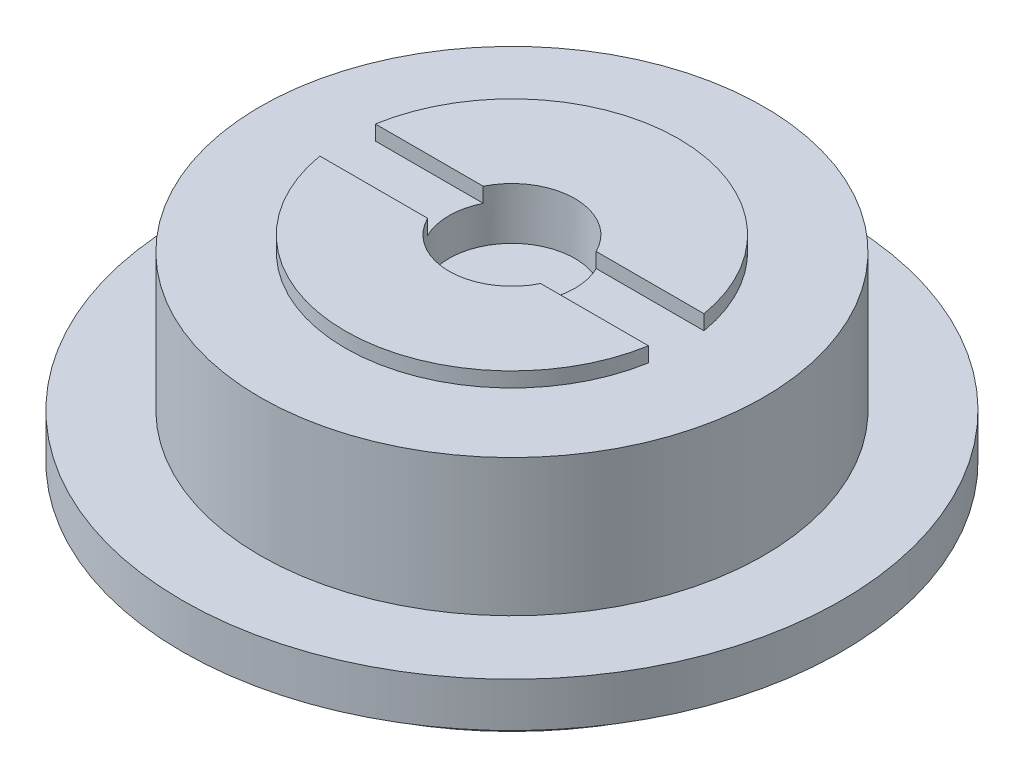
SolidWorks part; units mm, degrees
material "PP Copolymer"
ref_plane "Front Plane" through (0, 0, 0) normal (0, 0, 1) x (1, 0, 0)
ref_plane "Top Plane" through (0, 0, 0) normal (0, 1, 0) x (1, 0, 0)
ref_plane "Right Plane" through (0, 0, 0) normal (1, 0, 0) x (0, 0, -1)
sketch "BaseS" plane through (0, 0, 0) normal (0, 1, 0) x (1, 0, 0)
  circle A0 centre (0, 0) radius 8.9
  dimension "Dia" = 17.8
extrude "Base" add sketch "BaseS" against normal blind 1.2
sketch "O-RingCaptureS" plane through (0, 0, 0) normal (0, 1, 0) x (1, 0, 0)
  circle A0 centre (0, 0) radius 6.8
  circle A1 centre (0, 0) radius 8.9 construction
  dimension "RefDia" = 13.6
  dimension "DiaControl" = 2.1
extrude "O-RingCapture" add sketch "O-RingCaptureS" along normal blind 3.7
sketch "SealingFaceS" plane through (0, 3.7, 0) normal (0, 1, 0) x (1, 0, 0)
  circle A0 centre (0, 0) radius 4.5
  circle A1 centre (0, 0) radius 6.8 construction
  dimension "RefDia" = 9
  dimension "DiaControl" = 2.3
extrude "SealingFace" add sketch "SealingFaceS" along normal blind 0.4
sketch "SlotCutS" plane through (0, 4.1, 0) normal (0, 1, 0) x (1, 0, 0)
  line L1 (-4.5, 0.75) -> (4.5, 0.75)
  line L2 (-4.5, 0.75) -> (-4.5, -0.75)
  line L3 (-4.5, -0.75) -> (4.5, -0.75)
  line L4 (4.5, 0.75) -> (4.5, -0.75)
  line L5 (-4.5, 0.75) -> (4.5, -0.75) construction
  line L6 (-4.5, -0.75) -> (4.5, 0.75) construction
  circle A0 centre (0, 0) radius 4.5 construction
  point P0 (0, 0)
  dimension "SlotWidth" = 1.5
extrude "SlotCut" cut sketch "SlotCutS" against normal up to surface (0.4 mm away) up to face at (0, 3.7, 4.5)
sketch "BottomBaseS" plane through (0, -1.2, 0) normal (0, -1, 0) x (1, 0, 0)
  circle A0 centre (0, 0) radius 7.8
  circle A1 centre (0, 0) radius 8.9 construction
  dimension "RefDia" = 15.6
  dimension "DiaControl" = 1.1
extrude "BottomBase" add sketch "BottomBaseS" along normal blind 0.8
sketch "TopBoreS" plane through (0, 4.1, 0) normal (0, 1, 0) x (1, 0, 0)
  circle A0 centre (0, 0) radius 1.7
  dimension "Dia" = 3.4
extrude "TopBore" cut sketch "TopBoreS" against normal blind 1.4
sketch "BottomBoreS" plane through (0, -2, 0) normal (0, -1, 0) x (1, 0, 0)
  circle A0 centre (0, 0) radius 5.5
  circle A1 centre (0, 0) radius 7.8 construction
  dimension "RefDia" = 11
  dimension "DiaControl" = 2.3
extrude "BottomBore" cut sketch "BottomBoreS" against normal blind 4.4
sketch "CentralCylinderS" plane through (0, 2.4, 0) normal (0, -1, 0) x (-1, 0, 0)
  circle A0 centre (0, 0) radius 2.5
  dimension "Dia" = 5
extrude "CentralCylinder" add sketch "CentralCylinderS" along normal offset from surface (2.6 mm away) 1.8 up to face at (0, -2, -5.5)
sketch "CylinderBoreS" plane through (0, -0.2, 0) normal (0, -1, 0) x (-1, 0, 0)
  circle A0 centre (0, 0) radius 1.5
  circle A1 centre (0, 0) radius 2.5 construction
  dimension "RefDia" = 3
  dimension "DiaControl" = 1
extrude "CylinderBore" cut sketch "CylinderBoreS" against normal blind 0.6
sketch "RibS" plane through (0, 2.4, 0) normal (0, -1, 0) x (-1, 0, 0)
  line L0 (0, 0) -> (0, -2.5) construction
  line L2 (0.625, -5.4644) -> (0.625, -2.4206)
  line L4 (-0.625, -5.4644) -> (-0.625, -2.4206)
  circle A0 centre (0, 0) radius 2.5 construction
  circle A2 centre (0, 0) radius 5.5 construction
  arc A3 (-0.625, -2.4206) -> (0.625, -2.4206) centre (0, 0) ccw
  arc A4 (-0.625, -5.4644) -> (0.625, -5.4644) centre (0, 0) ccw
  point P0 (0, -2.5)
  point P7 (0.9985, -2.2919)
  point P10 (0.8285, -5.7166)
  dimension "Width" = 1.25
extrude "Rib" add sketch "RibS" along normal up to surface (4.4 mm away) up to face at (0, -2, -5.5)
pattern_circular "RibCP" count 8 over 360 about axis through (0, 0, 0) along (0, 1, 0) of "Rib"
sketch "RibCutS" plane through (0, -2, 0) normal (0, -1, 0) x (1, 0, 0)
  line L0 (0.625, 2.4206) -> (0.625, 5.4644) construction
  line L1 (-0.625, 7.8) -> (0.625, 7.8)
  line L2 (-0.625, 7.8) -> (-0.625, 4.5)
  line L3 (-0.625, 4.5) -> (0.625, 4.5)
  line L4 (0.625, 7.8) -> (0.625, 4.5)
  line L5 (-0.625, 5.4644) -> (-0.625, 2.4206) construction
  arc A0 (0.625, 2.4206) -> (-0.625, 2.4206) centre (0, 0) ccw construction
  circle A1 centre (0, 0) radius 7.8 construction
  point P9 (0, 2.5)
  dimension "LengthControl" = 2
extrude "RibCut" cut sketch "RibCutS" against normal blind 0.2
pattern_circular "RibCutCP" count 4 over 360 about axis through (0, 0, 0) along (0, 1, 0) of "RibCut"
